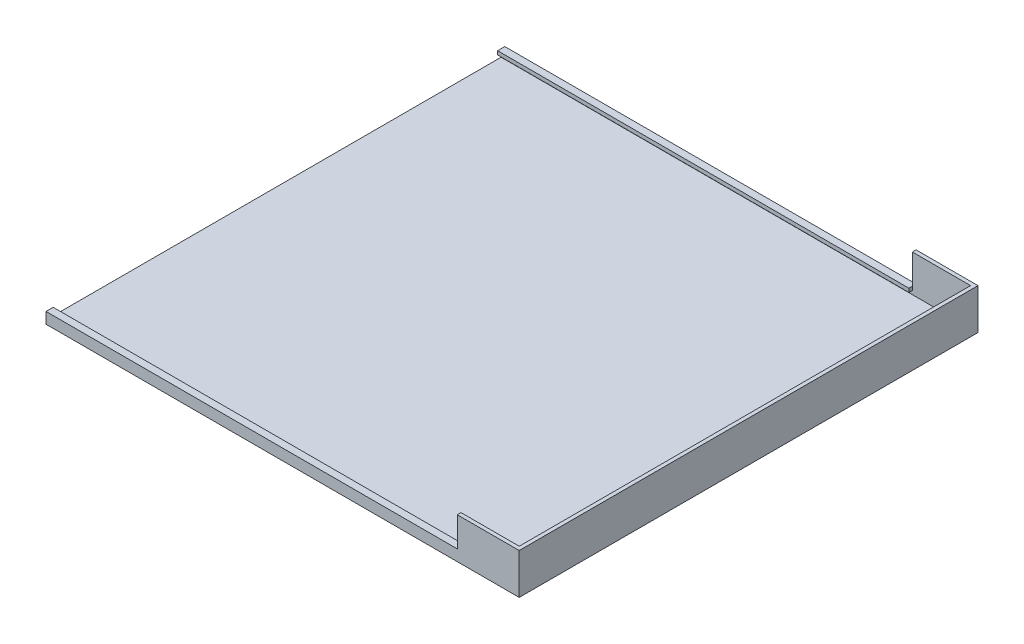
SolidWorks part; units mm, degrees
ref_plane "Front Plane" through (0, 0, 0) normal (0, 0, 1) x (1, 0, 0)
ref_plane "Top Plane" through (0, 0, 0) normal (0, 1, 0) x (1, 0, 0)
ref_plane "Right Plane" through (0, 0, 0) normal (1, 0, 0) x (0, 0, -1)
sketch "Sketch1" plane through (0, 0, 0) normal (0, 1, 0) x (1, 0, 0)
  line L1 (-128, 124.1) -> (128, 124.1)
  line L2 (-128, 124.1) -> (-128, -124.1)
  line L3 (-128, -124.1) -> (128, -124.1)
  line L4 (128, 124.1) -> (128, -124.1)
  line L5 (-128, 124.1) -> (128, -124.1) construction
  line L6 (-128, -124.1) -> (128, 124.1) construction
  point P0 (0, 0)
  dimension "D1" = 256
  dimension "D2" = 248.2
extrude "Boss-Extrude1" add sketch "Sketch1" along normal blind 2
sketch "Sketch2" plane through (0, 2, 0) normal (0, 1, 0) x (1, 0, 0)
  line L0 (128, -124.1) -> (128, 124.1) construction
  line L1 (-128, -124.1) -> (128, -124.1)
  line L2 (-128, -124.1) -> (-128, -122.1)
  line L3 (-128, -122.1) -> (128, -122.1)
  line L4 (128, -124.1) -> (128, -122.1)
  line L6 (-128, 124.1) -> (128, 124.1)
  line L7 (-128, 124.1) -> (-128, 122.1)
  line L8 (-128, 122.1) -> (128, 122.1)
  line L9 (128, 124.1) -> (128, 122.1)
  dimension "D1" = 2
  dimension "D2" = 2
extrude "Boss-Extrude2" add sketch "Sketch2" along normal blind 4
sketch "Sketch3" plane through (0, 0, 122.1) normal (0, 0, -1) x (-1, 0, 0)
  line L0 (128, 6) -> (128, 0) construction
  line L1 (-128, 6) -> (128, 6)
  line L2 (-128, 6) -> (-128, 4.0006)
  line L3 (-128, 4.0006) -> (128, 4.0006)
  line L4 (128, 6) -> (128, 4.0006)
extrude "Boss-Extrude3" add sketch "Sketch3" along normal blind 1.89
sketch "Sketch4" plane through (0, 0, -122.1) normal (0, 0, 1) x (1, 0, 0)
  line L0 (128, 6) -> (128, 2) construction
  line L1 (-128, 6) -> (128, 6)
  line L2 (-128, 6) -> (-128, 4)
  line L3 (-128, 4) -> (128, 4)
  line L4 (128, 6) -> (128, 4)
extrude "Boss-Extrude4" add sketch "Sketch4" along normal blind 1.89
sketch "Sketch5" plane through (0, 2, 0) normal (0, 1, 0) x (1, 0, 0)
  line L0 (-128, -124.1) -> (94.5, -124.1) construction
  line L1 (-128, -124.1) -> (128, -124.1) construction
  line L2 (94.5, -124.1) -> (128, -124.1)
  line L3 (128, -124.1) -> (128, -120.21)
  line L4 (128, -120.21) -> (94.5, -120.21)
  line L5 (-128, -120.21) -> (128, -120.21) construction
  line L6 (94.5, -120.21) -> (94.5, -124.1)
  line L7 (94.5, 124.1) -> (94.5, 120.21)
  line L8 (128, 124.1) -> (-128, 124.1) construction
  line L9 (128, 120.21) -> (-128, 120.21) construction
  line L10 (94.5, 120.21) -> (128, 120.21)
  line L11 (128, 120.21) -> (128, 124.1)
  line L12 (128, 124.1) -> (94.5, 124.1)
  dimension "D1" = 222.5
extrude "Cut-Extrude1" cut sketch "Sketch5" along normal blind 10
sketch "Sketch6" plane through (0, 2, 0) normal (0, 1, 0) x (1, 0, 0)
  line L0 (94.5, -124.1) -> (94.5, -122.1)
  line L1 (94.5, -122.1) -> (126, -122.1)
  line L2 (94.5, -124.1) -> (128, -124.1)
  line L3 (128, -124.1) -> (128, 124.1)
  line L4 (128, 124.1) -> (94.5, 124.1)
  line L5 (126, -122.1) -> (126, 122.1)
  line L6 (126, 122.1) -> (126, 124.1) construction
  line L7 (126, 122.1) -> (94.5, 122.1)
  line L9 (94.5, 122.1) -> (94.5, 124.1)
  line L11 (126, 122.1) -> (128, 122.1) construction
  dimension "D1" = 31.5
  dimension "D2" = 2
  dimension "D3" = 2
extrude "Boss-Extrude5" add sketch "Sketch6" along normal blind 20
